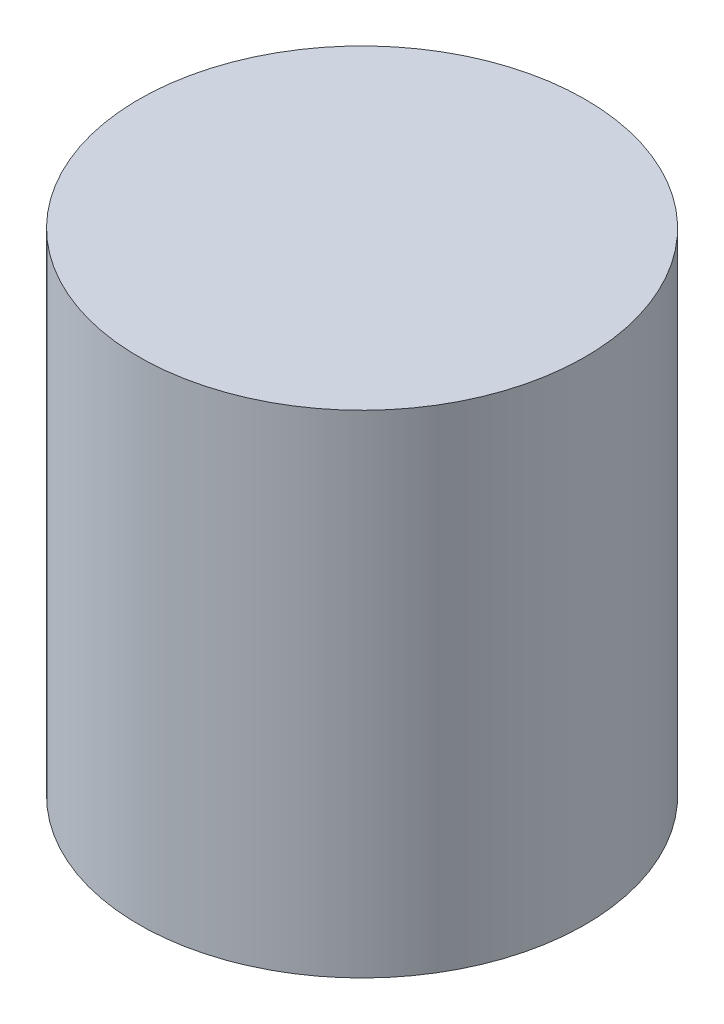
SolidWorks part; units mm, degrees
ref_plane "前视基准面" through (0, 0, 0) normal (0, 0, 1) x (1, 0, 0)
ref_plane "上视基准面" through (0, 0, 0) normal (0, 1, 0) x (1, 0, 0)
ref_plane "右视基准面" through (0, 0, 0) normal (1, 0, 0) x (0, 0, -1)
sketch "草图1" plane through (0, 0, 0) normal (0, 1, 0) x (1, 0, 0)
  circle A0 centre (-15.9458, 10.6013) radius 2.95
  point P2 (0, 0)
extrude "凸台-拉伸2" add sketch "草图1" along normal blind 6.5 contours A0
